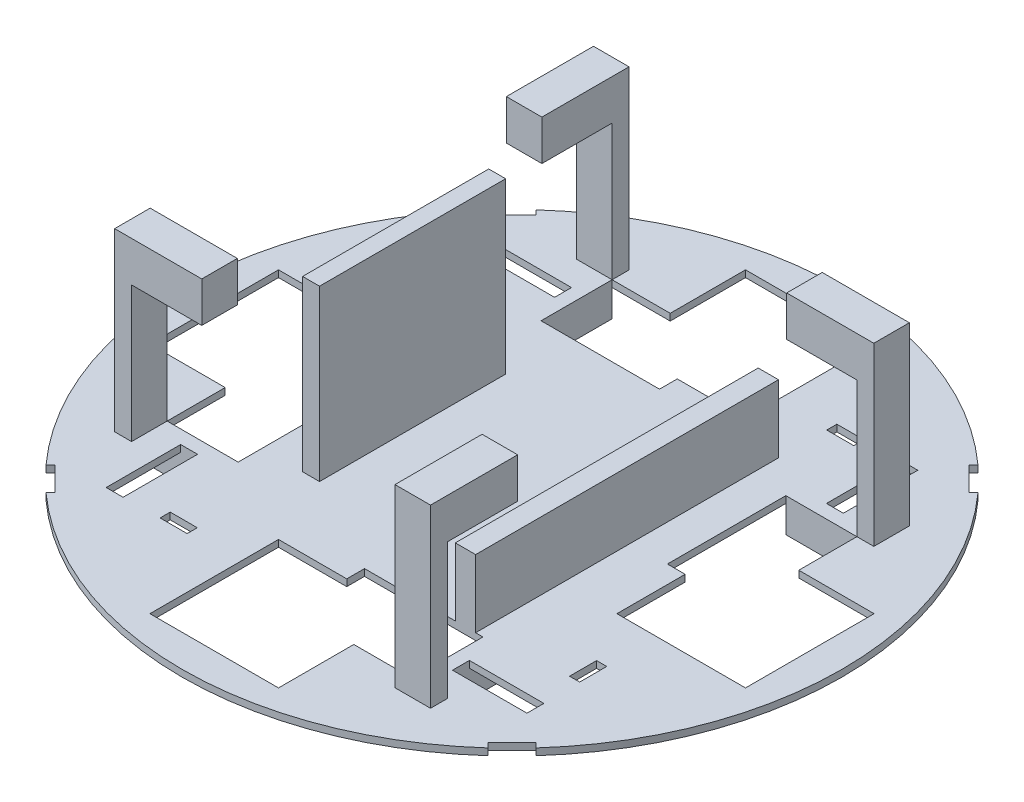
SolidWorks part; units mm, degrees
material "Custom Plastic"
ref_plane "Front Plane" through (0, 0, 0) normal (0, 0, 1) x (1, 0, 0)
ref_plane "Top Plane" through (0, 0, 0) normal (0, 1, 0) x (1, 0, 0)
ref_plane "Right Plane" through (0, 0, 0) normal (1, 0, 0) x (0, 0, -1)
sketch "Sketch1" plane through (0, 0, 0) normal (0, 1, 0) x (1, 0, 0)
  circle A0 centre (0, 0) radius 97.5
  dimension "D1" = 195
extrude "Plate" add sketch "Sketch1" along normal blind 2
sketch "Sketch2" plane through (0, 2, 0) normal (0, 1, 0) x (1, 0, 0)
  line L0 (50, 19) -> (88, 19)
  line L1 (-19, 50) -> (19, 50)
  line L2 (-19, 50) -> (-19, 88)
  line L3 (-19, 88) -> (19, 88)
  line L4 (19, 50) -> (19, 88)
  line L5 (50, 19) -> (50, -19)
  line L6 (50, -19) -> (88, -19)
  line L7 (88, 19) -> (88, -19)
  line L8 (19, -50) -> (19, -88)
  line L9 (19, -50) -> (-19, -50)
  line L10 (-19, -50) -> (-19, -88)
  line L11 (19, -88) -> (-19, -88)
  line L12 (-50, -19) -> (-88, -19)
  line L13 (-50, -19) -> (-50, 19)
  line L14 (-50, 19) -> (-88, 19)
  line L15 (-88, -19) -> (-88, 19)
  point P4 (0, 50)
  point P21 (0, 0)
  dimension "D1" = 50
  dimension "D2" = 38
  dimension "D3" = 38
  dimension "D4" = 4
extrude "Fin Clearances" cut sketch "Sketch2" against normal blind 2
sketch "Sketch3" plane through (0, 0, 0) normal (0, -1, 0) x (1, 0, 0)
  line L5 (-31.9184, -65.5) -> (-35.9184, -65.5) construction
  line L6 (-35.9184, -47) -> (-35.9184, -63.5) construction
  line L10 (-36.1684, -65.75) -> (-19, -65.75)
  line L11 (-36.1684, -65.75) -> (-36.1684, -44.75)
  line L12 (-36.1684, -44.75) -> (-19, -44.75)
  line L13 (-19, -65.75) -> (-19, -44.75)
  dimension "D1" = 21
  dimension "D2" = 0.25
  dimension "D3" = 0.25
extrude "Servo Clearance" cut sketch "Sketch3" against normal up to surface (2 mm away) up to face at (0, 2, -69)
sketch "Sketch4" plane through (0, 0, 0) normal (0, -1, 0) x (1, 0, 0)
  line L0 (-19, -44.75) -> (-36.1684, -44.75) construction
  line L1 (-36.1684, -65.75) -> (-40.1684, -65.75)
  line L2 (-36.1684, -65.75) -> (-36.1684, -44.75)
  line L3 (-36.1684, -44.75) -> (-40.1684, -44.75)
  line L4 (-40.1684, -65.75) -> (-40.1684, -44.75)
  dimension "D1" = 4
extrude "Servo Lip - Bottom" add sketch "Sketch4" along normal blind 8
sketch "Sketch5" plane through (0, 2, 0) normal (0, 1, 0) x (1, 0, 0)
  line L1 (-36.1684, 65.75) -> (-46.6684, 65.75)
  line L2 (-36.1684, 65.75) -> (-36.1684, 70.75)
  line L3 (-36.1684, 70.75) -> (-46.6684, 70.75)
  line L4 (-46.6684, 65.75) -> (-46.6684, 70.75)
  dimension "D1" = 5
  dimension "D2" = 10.5
extrude "Servo Lip - Top Extrusion" add sketch "Sketch5" along normal blind 52
sketch "Sketch6" plane through (0, 0, -65.75) normal (0, 0, 1) x (1, 0, 0)
  line L0 (-36.1684, 54) -> (-36.1684, 2) construction
  line L1 (-46.6684, 54) -> (-36.1684, 54)
  line L2 (-46.6684, 54) -> (-46.6684, 42.1)
  line L3 (-46.6684, 42.1) -> (-36.1684, 42.1)
  line L4 (-36.1684, 54) -> (-36.1684, 42.1)
  line L5 (-35.9184, 41.85) -> (-64.9184, 41.85) construction
  dimension "D1" = 0.25
extrude "Servo Lip - Top" add sketch "Sketch6" along normal up to surface (20.75 mm away)
sketch "Sketch7" plane through (0, 0, 0) normal (0, -1, 0) x (1, 0, 0)
  line L0 (-19, -44.75) -> (-36.1684, -44.75) construction
  line L1 (-36.1684, -65.75) -> (-1.1684, -65.75)
  line L2 (-36.1684, -65.75) -> (-36.1684, -44.75)
  line L3 (-36.1684, -44.75) -> (-1.1684, -44.75)
  line L4 (-1.1684, -65.75) -> (-1.1684, -44.75)
  dimension "D1" = 35
extrude "Servo Clearance for Insertion" cut sketch "Sketch7" against normal up to surface (2 mm away) up to face at (-23.0009, 2, -64.1667)
pattern_circular "4 Servo Lip Extrusions" count 4 over 360 about axis through (0, 0, 0) along (0, 1, 0) of "Servo Clearance", "Servo Lip - Bottom", "Servo Lip - Top Extrusion", "Servo Clearance for Insertion"
sketch "Sketch8" plane through (-65.75, 0, 0) normal (1, 0, 0) x (0, 0, -1)
  line L0 (-36.1684, 54) -> (-36.1684, 2) construction
  line L1 (-46.6684, 54) -> (-36.1684, 54)
  line L2 (-46.6684, 54) -> (-46.6684, 42.1)
  line L3 (-46.6684, 42.1) -> (-36.1684, 42.1)
  line L4 (-36.1684, 54) -> (-36.1684, 42.1)
  line L5 (-35.9184, 41.85) -> (-64.9184, 41.85) construction
  dimension "D1" = 0.25
extrude "Boss-Extrude6" add sketch "Sketch8" along normal up to surface (20.75 mm away)
sketch "Sketch9" plane through (0, 0, 65.75) normal (0, 0, -1) x (-1, 0, 0)
  line L0 (-46.6684, 54) -> (-46.6684, 2) construction
  line L1 (-36.1684, 54) -> (-46.6684, 54)
  line L2 (-36.1684, 54) -> (-36.1684, 42.1)
  line L3 (-36.1684, 42.1) -> (-46.6684, 42.1)
  line L4 (-46.6684, 54) -> (-46.6684, 42.1)
  line L5 (-35.9184, 41.85) -> (-64.9184, 41.85) construction
  dimension "D1" = 0.25
extrude "Boss-Extrude7" add sketch "Sketch9" along normal up to surface (20.75 mm away)
sketch "Sketch10" plane through (65.75, 0, 0) normal (-1, 0, 0) x (0, 0, 1)
  line L0 (-36.1684, 54) -> (-36.1684, 2) construction
  line L1 (-46.6684, 54) -> (-36.1684, 54)
  line L2 (-46.6684, 54) -> (-46.6684, 42.1)
  line L3 (-46.6684, 42.1) -> (-36.1684, 42.1)
  line L4 (-36.1684, 54) -> (-36.1684, 42.1)
  line L5 (-35.9184, 41.85) -> (-64.9184, 41.85) construction
  dimension "D1" = 0.25
extrude "Boss-Extrude8" add sketch "Sketch10" along normal up to surface (20.75 mm away)
sketch "Sketch11" plane through (0, 2, 0) normal (0, 1, 0) x (1, 0, 0)
  line L0 (-27.75, 40) -> (-27.75, -40) construction
  line L1 (-32.75, -29.1273) -> (-27.75, -29.1273)
  line L2 (-32.75, -29.1273) -> (-32.75, 25.8727)
  line L3 (-32.75, 25.8727) -> (-27.75, 25.8727)
  line L4 (-27.75, -29.1273) -> (-27.75, 25.8727)
  dimension "D1" = 55
  dimension "D2" = 5
extrude "EBox Lid Support" add sketch "Sketch11" along normal blind 50
sketch "Sketch12" plane through (0, 0, 0) normal (0, -1, 0) x (1, 0, 0)
  line L0 (0, 0) -> (-68.9429, 68.9429) construction
  line L1 (-71.0642, 63.9932) -> (-63.9932, 71.0642)
  line L2 (-71.0642, 63.9932) -> (-72.4784, 65.4074)
  line L3 (-63.9932, 71.0642) -> (-65.4074, 72.4784)
  line L4 (-72.4784, 65.4074) -> (-65.4074, 72.4784)
  line L5 (0, 0) -> (0, 18.8491) construction
  circle A0 centre (0, 0) radius 97.5 construction
  point P5 (-67.5287, 67.5287)
  dimension "D1" = 45
  dimension "D2" = 2
  dimension "D3" = 10
extrude "Cut-Extrude4" cut sketch "Sketch12" against normal blind 2
pattern_circular "Clip Clearances" count 4 over 360 about axis through (0, 0, 0) along (0, 1, 0) of "Cut-Extrude4"
sketch "Sketch13" plane through (0, 2, 0) normal (0, 1, 0) x (1, 0, 0)
  line L0 (27.75, -40) -> (27.75, 40) construction
  line L1 (34, -44.75) -> (28, -44.75)
  line L2 (34, -44.75) -> (34, 44.75)
  line L3 (34, 44.75) -> (28, 44.75)
  line L4 (28, -44.75) -> (28, 44.75)
  line L5 (1.1684, -44.75) -> (36.1684, -44.75) construction
  dimension "D1" = 6
  dimension "D2" = 89.5
  dimension "D3" = 0.25
extrude "EBox Bottom Support" add sketch "Sketch13" along normal blind 20
sketch "Sketch14" plane through (0, 0, 0) normal (0, -1, 0) x (1, 0, 0)
  line L0 (40.1684, 44.75) -> (40.1684, 65.75) construction
  line L1 (40.1684, 52.75) -> (62.1684, 52.75)
  line L2 (40.1684, 52.75) -> (40.1684, 57.75)
  line L3 (40.1684, 57.75) -> (62.1684, 57.75)
  line L4 (62.1684, 52.75) -> (62.1684, 57.75)
  line L5 (40.1684, 44.75) -> (40.1684, 65.75) construction
  line L6 (50, 19) -> (88, 19) construction
  line L7 (62, 42) -> (59, 42)
  line L8 (62, 42) -> (62, 34)
  line L9 (62, 34) -> (59, 34)
  line L10 (59, 42) -> (59, 34)
  line L11 (50, -1.1684) -> (50, 19) construction
  point P6 (40.1684, 55.25)
  point P9 (40.1684, 55.25)
  dimension "D1" = 22
  dimension "D2" = 5
  dimension "D3" = 8
  dimension "D4" = 3
  dimension "D5" = 15
  dimension "D6" = 9
extrude "Cut-Extrude5" cut sketch "Sketch14" against normal blind 10
pattern_circular "CirPattern1" count 4 over 360 about axis through (0, 0, 0) along (0, 1, 0) of "Cut-Extrude5"
